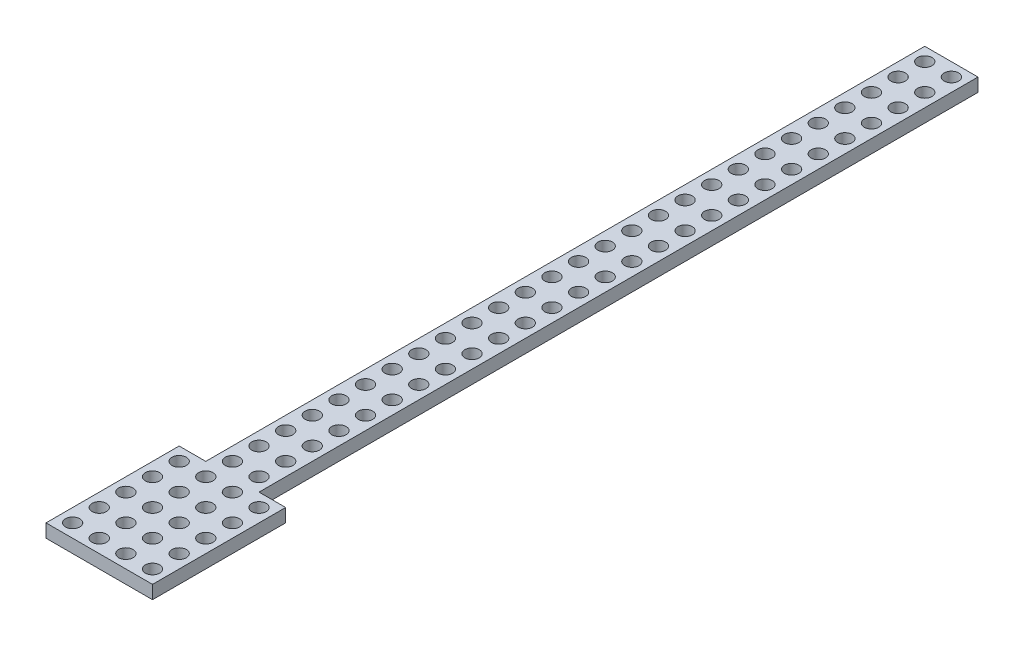
SolidWorks part; units mm, degrees
ref_plane "Front Plane" through (0, 0, 0) normal (0, 0, 1) x (1, 0, 0)
ref_plane "Top Plane" through (0, 0, 0) normal (0, 1, 0) x (1, 0, 0)
ref_plane "Right Plane" through (0, 0, 0) normal (1, 0, 0) x (0, 0, -1)
sketch "Sketch1" plane through (0, 0, 0) normal (0, 1, 0) x (1, 0, 0)
  line L1 (-25.4, -203.2) -> (25.4, -203.2)
  line L2 (-25.4, -203.2) -> (-25.4, 203.2)
  line L3 (-25.4, 203.2) -> (25.4, 203.2)
  line L4 (25.4, -203.2) -> (25.4, 203.2)
  line L5 (-25.4, -203.2) -> (25.4, 203.2) construction
  line L6 (-25.4, 203.2) -> (25.4, -203.2) construction
  circle A0 centre (-19.05, 196.85) radius 3.429
  circle A1 centre (-6.35, 196.85) radius 3.429
  circle A2 centre (6.35, 196.85) radius 3.429
  circle A3 centre (19.05, 196.85) radius 3.429
  circle A4 centre (-6.35, 184.15) radius 3.429
  circle A5 centre (6.35, 184.15) radius 3.429
  circle A6 centre (19.05, 184.15) radius 3.429
  circle A7 centre (-6.35, 171.45) radius 3.429
  circle A8 centre (6.35, 171.45) radius 3.429
  circle A9 centre (19.05, 171.45) radius 3.429
  circle A10 centre (-6.35, 158.75) radius 3.429
  circle A11 centre (6.35, 158.75) radius 3.429
  circle A12 centre (19.05, 158.75) radius 3.429
  circle A13 centre (-6.35, 146.05) radius 3.429
  circle A14 centre (6.35, 146.05) radius 3.429
  circle A15 centre (19.05, 146.05) radius 3.429
  circle A16 centre (-6.35, 133.35) radius 3.429
  circle A17 centre (6.35, 133.35) radius 3.429
  circle A18 centre (19.05, 133.35) radius 3.429
  circle A19 centre (-6.35, 120.65) radius 3.429
  circle A20 centre (6.35, 120.65) radius 3.429
  circle A21 centre (19.05, 120.65) radius 3.429
  circle A22 centre (-6.35, 107.95) radius 3.429
  circle A23 centre (6.35, 107.95) radius 3.429
  circle A24 centre (19.05, 107.95) radius 3.429
  circle A25 centre (-6.35, 95.25) radius 3.429
  circle A26 centre (6.35, 95.25) radius 3.429
  circle A27 centre (19.05, 95.25) radius 3.429
  circle A28 centre (-6.35, 82.55) radius 3.429
  circle A29 centre (6.35, 82.55) radius 3.429
  circle A30 centre (19.05, 82.55) radius 3.429
  circle A31 centre (-6.35, 69.85) radius 3.429
  circle A32 centre (6.35, 69.85) radius 3.429
  circle A33 centre (19.05, 69.85) radius 3.429
  circle A34 centre (-6.35, 57.15) radius 3.429
  circle A35 centre (6.35, 57.15) radius 3.429
  circle A36 centre (19.05, 57.15) radius 3.429
  circle A37 centre (-6.35, 44.45) radius 3.429
  circle A38 centre (6.35, 44.45) radius 3.429
  circle A39 centre (19.05, 44.45) radius 3.429
  circle A40 centre (-6.35, 31.75) radius 3.429
  circle A41 centre (6.35, 31.75) radius 3.429
  circle A42 centre (19.05, 31.75) radius 3.429
  circle A43 centre (-6.35, 19.05) radius 3.429
  circle A44 centre (6.35, 19.05) radius 3.429
  circle A45 centre (19.05, 19.05) radius 3.429
  circle A46 centre (-6.35, 6.35) radius 3.429
  circle A47 centre (6.35, 6.35) radius 3.429
  circle A48 centre (19.05, 6.35) radius 3.429
  circle A49 centre (-6.35, -6.35) radius 3.429
  circle A50 centre (6.35, -6.35) radius 3.429
  circle A51 centre (19.05, -6.35) radius 3.429
  circle A52 centre (-6.35, -19.05) radius 3.429
  circle A53 centre (6.35, -19.05) radius 3.429
  circle A54 centre (19.05, -19.05) radius 3.429
  circle A55 centre (-6.35, -31.75) radius 3.429
  circle A56 centre (6.35, -31.75) radius 3.429
  circle A57 centre (19.05, -31.75) radius 3.429
  circle A58 centre (-6.35, -44.45) radius 3.429
  circle A59 centre (6.35, -44.45) radius 3.429
  circle A60 centre (19.05, -44.45) radius 3.429
  circle A61 centre (-19.05, 184.15) radius 3.429
  circle A62 centre (-19.05, 171.45) radius 3.429
  circle A63 centre (-19.05, 158.75) radius 3.429
  circle A64 centre (-19.05, 146.05) radius 3.429
  circle A65 centre (-19.05, 133.35) radius 3.429
  circle A66 centre (-19.05, 120.65) radius 3.429
  circle A67 centre (-19.05, 107.95) radius 3.429
  circle A68 centre (-19.05, 95.25) radius 3.429
  circle A69 centre (-19.05, 82.55) radius 3.429
  circle A70 centre (-19.05, 69.85) radius 3.429
  circle A71 centre (-19.05, 57.15) radius 3.429
  circle A72 centre (-19.05, 44.45) radius 3.429
  circle A73 centre (-19.05, 31.75) radius 3.429
  circle A74 centre (-19.05, 19.05) radius 3.429
  circle A75 centre (-19.05, 6.35) radius 3.429
  circle A76 centre (-19.05, -6.35) radius 3.429
  circle A77 centre (-19.05, -19.05) radius 3.429
  circle A78 centre (-19.05, -31.75) radius 3.429
  circle A79 centre (-19.05, -44.45) radius 3.429
  circle A80 centre (-19.05, -57.15) radius 3.429
  circle A81 centre (-6.35, -57.15) radius 3.429
  circle A82 centre (6.35, -57.15) radius 3.429
  circle A83 centre (19.05, -57.15) radius 3.429
  circle A84 centre (-19.05, -69.85) radius 3.429
  circle A85 centre (-6.35, -69.85) radius 3.429
  circle A86 centre (6.35, -69.85) radius 3.429
  circle A87 centre (19.05, -69.85) radius 3.429
  circle A88 centre (-19.05, -82.55) radius 3.429
  circle A89 centre (-6.35, -82.55) radius 3.429
  circle A90 centre (6.35, -82.55) radius 3.429
  circle A91 centre (19.05, -82.55) radius 3.429
  circle A92 centre (-19.05, -95.25) radius 3.429
  circle A93 centre (-6.35, -95.25) radius 3.429
  circle A94 centre (6.35, -95.25) radius 3.429
  circle A95 centre (19.05, -95.25) radius 3.429
  circle A96 centre (-19.05, -107.95) radius 3.429
  circle A97 centre (-6.35, -107.95) radius 3.429
  circle A98 centre (6.35, -107.95) radius 3.429
  circle A99 centre (19.05, -107.95) radius 3.429
  circle A100 centre (-19.05, -120.65) radius 3.429
  circle A101 centre (-6.35, -120.65) radius 3.429
  circle A102 centre (6.35, -120.65) radius 3.429
  circle A103 centre (19.05, -120.65) radius 3.429
  circle A104 centre (-19.05, -133.35) radius 3.429
  circle A105 centre (-6.35, -133.35) radius 3.429
  circle A106 centre (6.35, -133.35) radius 3.429
  circle A107 centre (19.05, -133.35) radius 3.429
  circle A108 centre (-19.05, -146.05) radius 3.429
  circle A109 centre (-6.35, -146.05) radius 3.429
  circle A110 centre (6.35, -146.05) radius 3.429
  circle A111 centre (19.05, -146.05) radius 3.429
  circle A112 centre (-19.05, -158.75) radius 3.429
  circle A113 centre (-6.35, -158.75) radius 3.429
  circle A114 centre (6.35, -158.75) radius 3.429
  circle A115 centre (19.05, -158.75) radius 3.429
  circle A116 centre (-19.05, -171.45) radius 3.429
  circle A117 centre (-6.35, -171.45) radius 3.429
  circle A118 centre (6.35, -171.45) radius 3.429
  circle A119 centre (19.05, -171.45) radius 3.429
  circle A120 centre (-19.05, -184.15) radius 3.429
  circle A121 centre (-6.35, -184.15) radius 3.429
  circle A122 centre (6.35, -184.15) radius 3.429
  circle A123 centre (19.05, -184.15) radius 3.429
  circle A124 centre (-19.05, -196.85) radius 3.429
  circle A125 centre (-6.35, -196.85) radius 3.429
  circle A126 centre (6.35, -196.85) radius 3.429
  circle A127 centre (19.05, -196.85) radius 3.429
  circle A160 centre (-19.05, -209.55) radius 3.429 [skipped]
  circle A161 centre (-6.35, -209.55) radius 3.429 [skipped]
  circle A162 centre (6.35, -209.55) radius 3.429 [skipped]
  circle A163 centre (19.05, -209.55) radius 3.429 [skipped]
  circle A164 centre (-19.05, -222.25) radius 3.429 [skipped]
  circle A165 centre (-6.35, -222.25) radius 3.429 [skipped]
  circle A166 centre (6.35, -222.25) radius 3.429 [skipped]
  circle A167 centre (19.05, -222.25) radius 3.429 [skipped]
  circle A168 centre (-19.05, -234.95) radius 3.429 [skipped]
  circle A169 centre (-6.35, -234.95) radius 3.429 [skipped]
  circle A170 centre (6.35, -234.95) radius 3.429 [skipped]
  circle A171 centre (19.05, -234.95) radius 3.429 [skipped]
  circle A172 centre (-19.05, -247.65) radius 3.429 [skipped]
  circle A173 centre (-6.35, -247.65) radius 3.429 [skipped]
  circle A174 centre (6.35, -247.65) radius 3.429 [skipped]
  circle A175 centre (19.05, -247.65) radius 3.429 [skipped]
  circle A176 centre (-19.05, -260.35) radius 3.429 [skipped]
  circle A177 centre (-6.35, -260.35) radius 3.429 [skipped]
  circle A178 centre (6.35, -260.35) radius 3.429 [skipped]
  circle A179 centre (19.05, -260.35) radius 3.429 [skipped]
  circle A180 centre (-19.05, -273.05) radius 3.429 [skipped]
  circle A181 centre (-6.35, -273.05) radius 3.429 [skipped]
  circle A182 centre (6.35, -273.05) radius 3.429 [skipped]
  circle A183 centre (19.05, -273.05) radius 3.429 [skipped]
  circle A184 centre (-19.05, -285.75) radius 3.429 [skipped]
  circle A185 centre (-6.35, -285.75) radius 3.429 [skipped]
  circle A186 centre (6.35, -285.75) radius 3.429 [skipped]
  circle A187 centre (19.05, -285.75) radius 3.429 [skipped]
  circle A188 centre (-19.05, -298.45) radius 3.429 [skipped]
  circle A189 centre (-6.35, -298.45) radius 3.429 [skipped]
  circle A190 centre (6.35, -298.45) radius 3.429 [skipped]
  circle A191 centre (19.05, -298.45) radius 3.429 [skipped]
  point P0 (0, 0)
  dimension "D3" = 6.858
  dimension "D1" = 50.8
  dimension "D2" = 406.4
  dimension "D4" = 6.35
  dimension "D5" = 6.35
  dimension "D6" = 4
  dimension "D7" = 40
extrude "Boss-Extrude1" add sketch "Sketch1" along normal blind 6.35
sketch "Sketch2" plane through (0, 6.35, 0) normal (0, 1, 0) x (1, 0, 0)
  line L0 (-12.7, 203.2) -> (-12.7, -139.7)
  line L1 (25.4, 203.2) -> (-25.4, 203.2) construction
  line L2 (-12.7, -139.7) -> (-25.4, -139.7)
  line L3 (-25.4, 203.2) -> (-25.4, -203.2) construction
  line L4 (-25.4, -139.7) -> (-25.4, -203.2)
  line L5 (-25.4, -203.2) -> (25.4, -203.2)
  line L6 (25.4, -203.2) -> (25.4, -139.7)
  line L7 (25.4, -203.2) -> (25.4, 203.2) construction
  line L8 (25.4, -139.7) -> (12.7, -139.7)
  line L9 (12.7, -139.7) -> (12.7, 203.2)
  line L10 (12.7, 203.2) -> (-12.7, 203.2)
  dimension "D1" = 12.7
  dimension "D2" = 25.4
  dimension "D3" = 63.5
extrude "Cut-Extrude1" cut sketch "Sketch2" against normal through all flip side to cut
